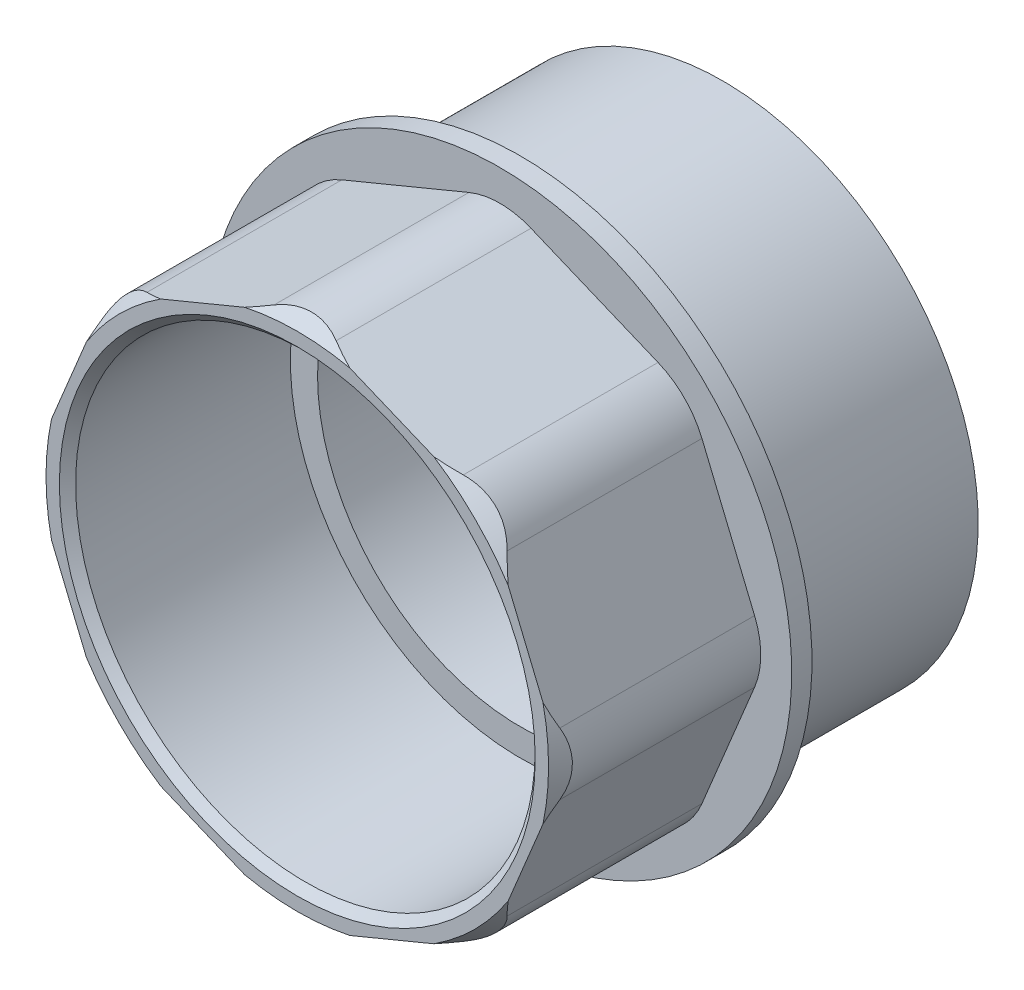
SolidWorks part; units mm, degrees
ref_plane "Płaszczyzna przednia" through (0, 0, 0) normal (0, 0, 1) x (1, 0, 0)
ref_plane "Płaszczyzna górna" through (0, 0, 0) normal (0, 1, 0) x (1, 0, 0)
ref_plane "Płaszczyzna prawa" through (0, 0, 0) normal (1, 0, 0) x (0, 0, -1)
sketch "Szkic1" plane through (0, 0, 0) normal (0, 0, 1) x (1, 0, 0)
  circle A1 centre (0, 0) radius 33
  dimension "D1" = 66
extrude "Dodanie-wyciągnięcie1" add sketch "Szkic1" against normal blind 25
sketch "Szkic2" plane through (0, 0, -25) normal (0, 0, -1) x (-1, 0, 0)
  circle A0 centre (0, 0) radius 36
  dimension "D1" = 72
extrude "Dodanie-wyciągnięcie2" add sketch "Szkic2" along normal blind 2.5
sketch "Szkic4" plane through (0, 0, -27.5) normal (0, 0, -1) x (-1, 0, 0)
  circle A0 centre (0, 0) radius 31.5
  dimension "D1" = 63
extrude "Dodanie-wyciągnięcie3" add sketch "Szkic4" along normal blind 25
sketch "Szkic10" plane through (0, 0, 0) normal (0, 0, 1) x (1, 0, 0)
  line L11 (0, 33) -> (-23.3345, 23.3345)
  line L12 (-23.3345, 23.3345) -> (-33, 0)
  line L13 (-33, 0) -> (-23.3345, -23.3345)
  line L14 (-23.3345, -23.3345) -> (0, -33)
  line L15 (0, -33) -> (23.3345, -23.3345)
  line L16 (23.3345, -23.3345) -> (33, 0)
  line L17 (33, 0) -> (23.3345, 23.3345)
  line L18 (23.3345, 23.3345) -> (0, 33)
  circle A1 centre (0, 0) radius 30.488 construction
  circle A9 centre (0, 0) radius 33 construction
  circle A10 centre (0, 0) radius 33
  point P20 (0, 0)
  circle M1 centre (0, 0) radius 33
sketch "Szkic11" plane through (0, 0, 0) normal (0, 0, 1) x (1, 0, 0)
  circle A0 centre (0, 0) radius 28.35
  dimension "D1" = 56.7
extrude "Wytnij-wyciągnięcie5" cut sketch "Szkic11" against normal blind 27.5
sketch "Szkic12" plane through (0, 0, -27.5) normal (0, 0, 1) x (1, 0, 0)
  circle A0 centre (0, 0) radius 25
  dimension "D1" = 50
extrude "Wytnij-wyciągnięcie6" cut sketch "Szkic12" against normal blind 27.5
sketch "Szkic13" plane through (0, 0, -52.5) normal (0, 0, -1) x (-1, 0, 0)
  circle A0 centre (0, 0) radius 28.35
  dimension "D1" = 56.7
extrude "Wytnij-wyciągnięcie7" cut sketch "Szkic13" against normal blind 8
chamfer "Sfazowanie1" distance 1 angle 45 1 edges at (28.35, 0, 0)
cosmetic thread "Oznaczenie gwintu1" parameters "D2"=56.71
chamfer "Sfazowanie2" distance 1 angle 45 1 edges at (-28.35, 0, -52.5)
extrude "Wytnij-wyciągnięcie11" cut sketch "Szkic10" against normal blind 25 contours L13 M1 | L12 M1 | L14 M1 | L15 M1 | L16 M1 | L17 M1 | L18 M1 | L11 M1
sketch "Szkic14" plane through (0, 0, 0) normal (1, 0, 0) x (0, 0, -1)
  line L3 (0, 0) -> (20.4015, 0) construction
  line L4 (0, 33) -> (0, 31)
  line L5 (0, 23.3345) -> (0, 33) construction
  line L6 (0, 31) -> (3, 33)
  line L7 (25, 33) -> (0, 33) construction
  line L8 (3, 33) -> (0, 33)
  dimension "D1" = 2
  dimension "D2" = 3
revolve "Wycięcie-obrót3" cut sketch "Szkic14" angle 360 about L3
fillet "Zaokrąglenie1" radius 10 8 edges at (-23.3345, 23.3345, -14) (0, 33, -14) (23.3345, 23.3345, -14) (33, 0, -14) (23.3345, -23.3345, -14) (0, -33, -14) (-23.3345, -23.3345, -14) (-33, 0, -14)
